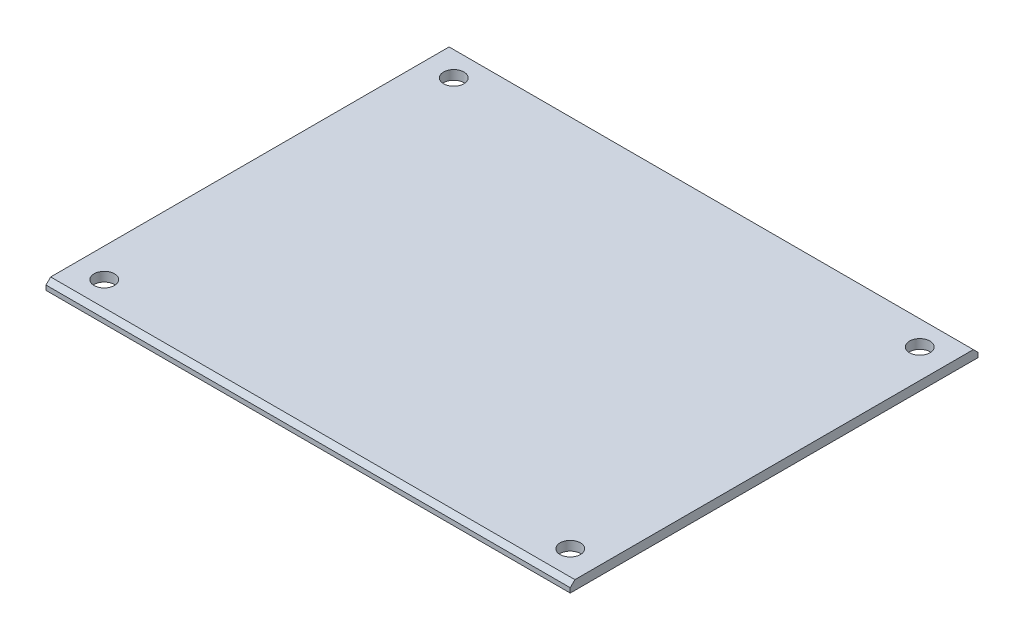
SolidWorks part; units mm, degrees
ref_plane "Front Plane" through (0, 0, 0) normal (0, 0, 1) x (1, 0, 0)
ref_plane "Top Plane" through (0, 0, 0) normal (0, 1, 0) x (1, 0, 0)
ref_plane "Right Plane" through (0, 0, 0) normal (1, 0, 0) x (0, 0, -1)
sketch "Sketch1" plane through (0, 0, 0) normal (0, 1, 0) x (1, 0, 0)
  line L1 (-45, 35) -> (45, 35)
  line L2 (-45, 35) -> (-45, -35)
  line L3 (-45, -35) -> (45, -35)
  line L4 (45, 35) -> (45, -35)
  line L5 (-45, 35) -> (45, -35) construction
  line L6 (-45, -35) -> (45, 35) construction
  point P0 (0, 0)
  dimension "D1" = 90
  dimension "D2" = 70
extrude "Boss-Extrude1" add sketch "Sketch1" along normal blind 1.6
sketch "Sketch2" plane through (0, 1.6, 0) normal (0, 1, 0) x (1, 0, 0)
  line L0 (-45, -35) -> (45, -35) construction
  line L1 (-45, 35) -> (-45, -35) construction
  line L2 (45, 35) -> (-45, 35) construction
  line L3 (45, -35) -> (45, 35) construction
  circle A0 centre (-40, -30) radius 1.75
  circle A1 centre (-40, 30) radius 1.75
  circle A2 centre (40, 30) radius 1.75
  circle A3 centre (40, -30) radius 1.75
  dimension "D1" = 3.5
  dimension "D2" = 5
  dimension "D3" = 5
  dimension "D4" = 5
  dimension "D5" = 5
extrude "Cut-Extrude1" cut sketch "Sketch2" against normal through all
chamfer "Chamfer1" distance 0.8 distance2 0.8 2 edges at (0, 1.6, -35) (0, 1.6, 35)
